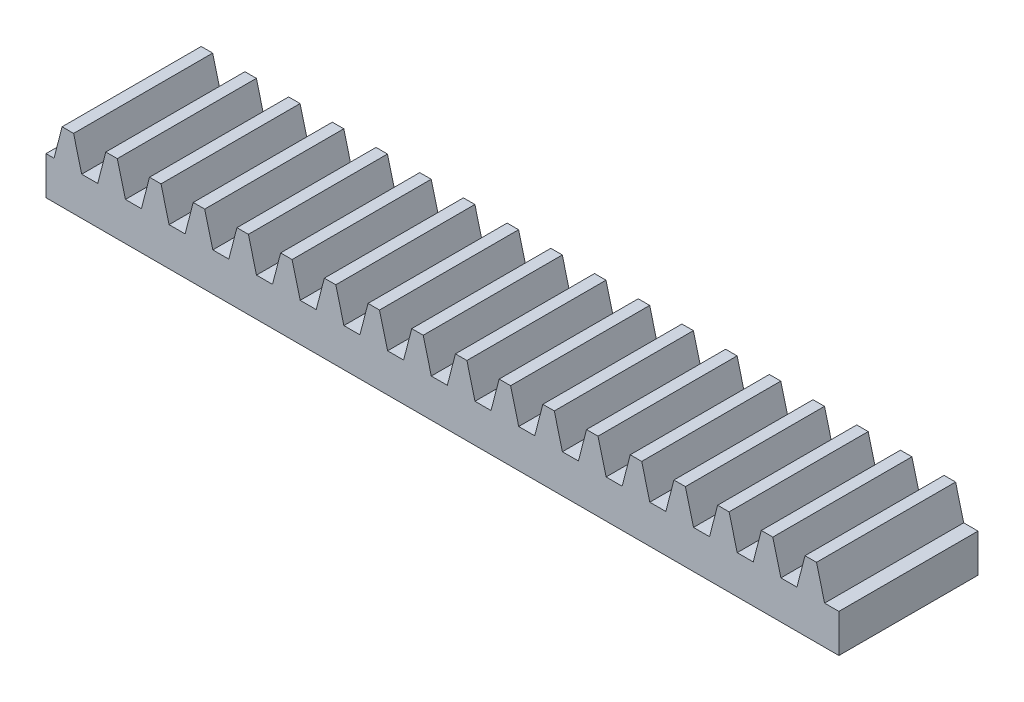
SolidWorks part; units mm, degrees
extrude "Blank" add sketch "BlankSke" against normal blind 10
sketch "BlankSke" plane through (0, 0, 0) normal (0, 0, 1) x (1, 0, 0)
  line L1 (0, 0) -> (57, 0)
  line L2 (0, 0) -> (0, 5)
  line L3 (0, 5) -> (57, 5)
  line L4 (57, 0) -> (57, 5)
  dimension "Length" = 57
  dimension "Blank_height" = 5
ref_plane "Plane1" through (0, 0, 0) normal (0, 0, 1) x (1, 0, 0)
ref_plane "Plane2" through (0, 0, 0) normal (0, 1, 0) x (1, 0, 0)
ref_plane "Plane3" through (0, 0, 0) normal (1, 0, 0) x (0, 0, -1)
other "Configuration Table"
sketch "HoldingSke" plane through (0, 0, 0) normal (0, 1, 0) x (1, 0, 0)
  line L0 (0, 0) -> (0.1392, 0.9903)
  line L1 (-15, 0) -> (100, 0) construction
  line L2 (0, 0) -> (-2.1039, 2.3779)
  line L3 (0, 0) -> (-11.863, 4.5341)
  line L4 (0, 0) -> (8.1152, 2.9537)
  line L5 (0, 0) -> (-23.7986, -8.8762)
  line L6 (0, 0) -> (-10.5278, -7.1032)
  line L9 (-67.7845, 28.3722) -> (-12.6001, 42.6439)
  line L10 (-76.2, 3.3779) -> (-72.2, 3.3779)
  line L11 (0, 0) -> (-10, 0)
  line L12 (-76.2, 101.6) -> (-76.162, 101.6)
  line L13 (24.9733, 27.94) -> (52.9518, 28.4284)
  line L14 (24.9733, 27.94) -> (24.9743, 27.94)
  line L15 (24.9733, 27.94) -> (100.4006, 29.5858)
  circle A0 centre (0, 0) radius 19.05
  circle A1 centre (0, 0) radius 2
  circle A2 centre (0, 0) radius 12.7
  dimension "MPH" = 4
  dimension "Diameter" = 38.1
  dimension "Num_teeth" = 20
  dimension "Pitch" = 1
  dimension "Show_teeth" = 998
  dimension "Thickness" = 12.7
  dimension "Ap" = 14.5
  dimension "Pitch_height" = 4
  dimension "Width" = 10
  dimension "Backlash" = 0.038
  dimension "Addendum_fac" = 1
  dimension "Dedendum_fac" = 1.25
  dimension "Clearance_fac" = 0.25
  dimension "Dedendum_add" = 0.001
  dimension "Length" = 57
  dimension "Module" = 1
sketch "TooCutSkeIll" plane through (0, 0, 0) normal (0, 0, 1) x (1, 0, 0)
  line L0 (-1.1503, 4.97) -> (-0.6248, 2.9382)
  line L1 (-0.3818, 2.75) -> (0.3818, 2.75)
  line L2 (0.6248, 2.9382) -> (1.1503, 4.97)
  line L3 (57, 5) -> (0, 5) construction
  line L4 (0, 0) -> (0, 64.897) construction
  line L5 (-13.208, 4) -> (12.954, 4) construction
  line L6 (0, 0) -> (57, 0) construction
  line L7 (0.8994, 4) -> (0.8994, 48.7463) construction
  line L8 (-0.8994, 4) -> (-0.8994, 48.7463) construction
  line L9 (1.189, 5) -> (1.189, 5.0254)
  line L10 (-1.189, 5) -> (-1.189, 5.0254)
  line L11 (-1.189, 5.0254) -> (1.189, 5.0254)
  arc A0 (0.3818, 2.75) -> (0.6248, 2.9382) centre (0.3818, 3.001) ccw
  arc A1 (-0.6248, 2.9382) -> (-0.3818, 2.75) centre (-0.3818, 3.001) ccw
  arc A2 (1.189, 5) -> (1.1503, 4.97) centre (1.189, 4.96) ccw
  arc A3 (-1.1503, 4.97) -> (-1.189, 5) centre (-1.189, 4.96) ccw
  dimension "Pitch_height" = 4
  dimension "Addendum_plus" = 1.0254
  dimension "Pressure_angle" = 14.5
  dimension "Gap_width" = 1.7988
  dimension "Dedendum" = 1.25
extrude "ToothCutIll" [suppressed] cut sketch "TooCutSkeIll" against normal through all
sketch "TooCutSkeSim" plane through (0, 0, 0) normal (0, 0, 1) x (1, 0, 0)
  line L0 (0.5761, 2.75) -> (-0.5761, 2.75)
  line L1 (1.1646, 5.0254) -> (0.5761, 2.75)
  line L2 (0, 17.4625) -> (0, 53.467) construction
  line L3 (1.1646, 5.0254) -> (-1.1646, 5.0254)
  line L6 (-1.1646, 5.0254) -> (-0.5761, 2.75)
  line L9 (-0.8994, 4) -> (0.8994, 4) construction
  line L10 (0, 0) -> (57, 0) construction
  line L11 (0.8994, 4) -> (0.8994, 53.467) construction
  line L12 (-0.8994, 4) -> (-0.8994, 53.467) construction
  dimension "Pitch_height" = 4
  dimension "Addendum_plus" = 1.0254
  dimension "Pressure_angle" = 14.5
  dimension "Gap_width" = 1.7988
  dimension "Dedendum" = 1.25
extrude "ToothCutSim" cut sketch "TooCutSkeSim" against normal through all
pattern_linear "TeethCuts" count 19 spacing 3.1416 along (1, 0, 0) of "ToothCutIll", "ToothCutSim"
equation "' \"Module@HoldingSke\" = 6.35"
equation "' \"Num_teeth@HoldingSke\" = 12"
equation "' \"Ap@HoldingSke\" =  20"
equation "' \"Ap@HoldingSke\" = 20"
equation "' \"Width@HoldingSke\" = 0.25 * 25.4"
equation "' \"Show_teeth@HoldingSke\" = 500"
equation "' \"Backlash@HoldingSke\" = 0.009 * 25.4"
equation "' \"Addendum_fac@HoldingSke\" = 1.0"
equation "' \"Dedendum_fac@HoldingSke\" = 1.25"
equation "' \"Dedendum_add@HoldingSke\" = 0.00005 * 25.4"
equation "' \"Clearance_fac@HoldingSke\" = 0.25"
equation "' \"Pitch_height@HoldingSke\" = 1 * 25.4"
equation "' \"Length@HoldingSke\" = 4.71 * 25.4"
equation "\"Pitch@HoldingSke\" = 1 / \"Module@HoldingSke\""
equation "\"MPH@HoldingSke\" = \"Dedendum_fac@HoldingSke\" / \"Pitch@HoldingSke\" + 2 * \"Dedendum_add@HoldingSke\" + 0.002 * 25.4"
equation "\"MPH@HoldingSke\" = ((sgn( \"MPH@HoldingSke\" - \"Pitch_height@HoldingSke\")+1)*( \"MPH@HoldingSke\" - \"Pitch_height@HoldingSke\"))/2 + \"Pitch_height@HoldingSke\""
equation "\"Blank_height@BlankSke\" = \"Pitch_height@HoldingSke\" + \"Addendum_fac@HoldingSke\"  / \"Pitch@HoldingSke\" "
equation "\"Length@BlankSke\" =  \"Length@HoldingSke\""
equation "\"Face_width@Blank\" = \"Width@HoldingSke\""
equation "\"Pressure_angle@TooCutSkeIll\" = \"Ap@HoldingSke\""
equation "\"Addendum_plus@TooCutSkeIll\" =  \"Addendum_fac@HoldingSke\"  / \"Pitch@HoldingSke\" + 0.001 *25.4"
equation "\"Dedendum@TooCutSkeIll\" = \"Dedendum_fac@HoldingSke\"  / \"Pitch@HoldingSke\""
equation "\"Pitch_height@TooCutSkeIll\" =  \"MPH@HoldingSke\""
equation "\"Gap_width@TooCutSkeIll\" = 3.14159265 / 2 / \"Pitch@HoldingSke\" + 6 * \"Backlash@HoldingSke\""
equation "\"Pressure_angle@TooCutSkeSim\" = \"Ap@HoldingSke\""
equation "\"Addendum_plus@TooCutSkeSim\" =  \"Addendum_fac@HoldingSke\"  / \"Pitch@HoldingSke\" + 0.001 * 25.4"
equation "\"Dedendum@TooCutSkeSim\" = \"Dedendum_fac@HoldingSke\"  / \"Pitch@HoldingSke\""
equation "\"Pitch_height@TooCutSkeSim\" =  \"MPH@HoldingSke\""
equation "\"Gap_width@TooCutSkeSim\" = 3.14159265 / 2 / \"Pitch@HoldingSke\" + 6 * \"Backlash@HoldingSke\""
equation "\"Root_fillet@TooCutSkeIll\" = \"Clearance_fac@HoldingSke\" / \"Pitch@HoldingSke\" + \"Dedendum_add@HoldingSke\""
equation "\"Break_rad@TooCutSkeIll\" = 0.02 / \"Pitch@HoldingSke\" * 2"
equation "\"Linear_pitch@TeethCuts\" = 3.14159265 / \"Pitch@HoldingSke\""
equation "\"Num_teeth@HoldingSke\" = int( ( \"Length@HoldingSke\" + 0 ) / (3.14159265 / \"Pitch@HoldingSke\")) + 0.9999  + 1"
equation " \"Num_teeth@TeethCuts\" = int( \"Show_teeth@HoldingSke\" ) + 1"
equation " \"Num_teeth@TeethCuts\" = ((sgn( \"Num_teeth@TeethCuts\" - \"Num_teeth@HoldingSke\" )-1)*( \"Num_teeth@TeethCuts\" - \"Num_teeth@HoldingSke\" ))/-2+ \"Num_teeth@HoldingSke\""
equation " \"Num_teeth@TeethCuts\" = ((sgn( \"Num_teeth@TeethCuts\" - 2.0)+1)*( \"Num_teeth@TeethCuts\" - 2.0))/2 +2.0"
